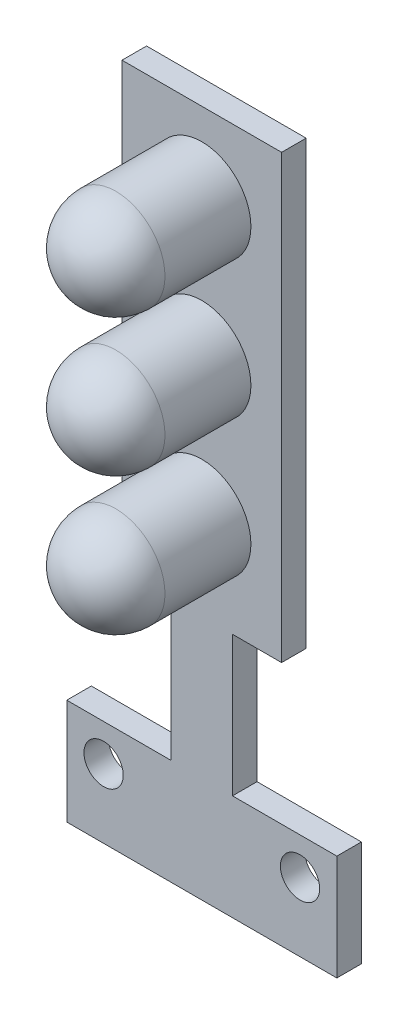
SolidWorks part; units mm, degrees
ref_plane "Alzado" through (0, 0, 0) normal (0, 0, 1) x (1, 0, 0)
ref_plane "Planta" through (0, 0, 0) normal (0, 1, 0) x (1, 0, 0)
ref_plane "Vista lateral" through (0, 0, 0) normal (1, 0, 0) x (0, 0, -1)
sketch "Croquis1" plane through (0, 0, 0) normal (0, 0, 1) x (1, 0, 0)
  line L0 (-6.5, 28) -> (-6.5, -8)
  line L1 (-6.5, -8) -> (-2.5, -8)
  line L2 (-2.5, -8) -> (-2.5, -19.4)
  line L3 (-2.5, -19.4) -> (-11, -19.4)
  line L4 (-11, -19.4) -> (-11, -28)
  line L5 (-11, -28) -> (11, -28)
  line L6 (0, -28) -> (0, 28)
  line L7 (6.5, 28) -> (-6.5, 28)
  line L8 (0, 32.2204) -> (0, -46.45) construction
  line L9 (11, -19.4) -> (11, -28)
  line L10 (2.5, -19.4) -> (11, -19.4)
  line L11 (2.5, -8) -> (2.5, -19.4)
  line L12 (6.5, -8) -> (2.5, -8)
  line L13 (6.5, 28) -> (6.5, -8)
  line L14 (-11, -23.7) -> (0, -23.7) construction
  line L15 (-8, -20.8) -> (-5.82, -20.8) construction
  line L16 (-9.6, -22.4) -> (-9.6, -21.0113) construction
  circle A0 centre (-8, -22.4) radius 1.6
  circle A1 centre (8, -22.4) radius 1.6
  point P5 (0, 0)
  dimension "D7" = 3.2
  dimension "D1" = 56
  dimension "D2" = 6.5
  dimension "D3" = 2.5
  dimension "D4" = 11
  dimension "D5" = 36
  dimension "D6" = 8.6
  dimension "D8" = 1.4
  dimension "D9" = 1.4
extrude "Saliente-Extruir1" add sketch "Croquis1" along normal blind 2 contours L6 L7 L0 L1 L2 L3 L4 L5 | L13 L7 L6 L5 L9 L10 L11 L12
sketch "Croquis2" plane through (0, 0, 2) normal (0, 0, 1) x (1, 0, 0)
  line L0 (0, 0) -> (0, 28) construction
  line L1 (6.5, 28) -> (-6.5, 28) construction
  line L2 (0, 25.5) -> (13.5255, 25.5) construction
  line L3 (0, 17.5) -> (12.5835, 17.5) construction
  line L4 (0, 14.3) -> (12.5835, 14.3) construction
  line L5 (0, 6.3) -> (13.5255, 6.3) construction
  line L6 (0, 3.1) -> (10.9139, 3.1) construction
  circle A0 centre (0, 21.5) radius 4
  circle A1 centre (0, 10.3) radius 4
  circle A2 centre (0, -0.9) radius 4
  dimension "D1" = 8
  dimension "D2" = 2.5
  dimension "D3" = 3.2
  dimension "D4" = 3.2
extrude "Saliente-Extruir2" add sketch "Croquis2" along normal blind 11
fillet "Redondeo1" radius 4 1 edges at (4, 21.5, 13)
fillet "Redondeo2" radius 4 2 edges at (4, -0.9, 13) (4, 10.3, 13)
